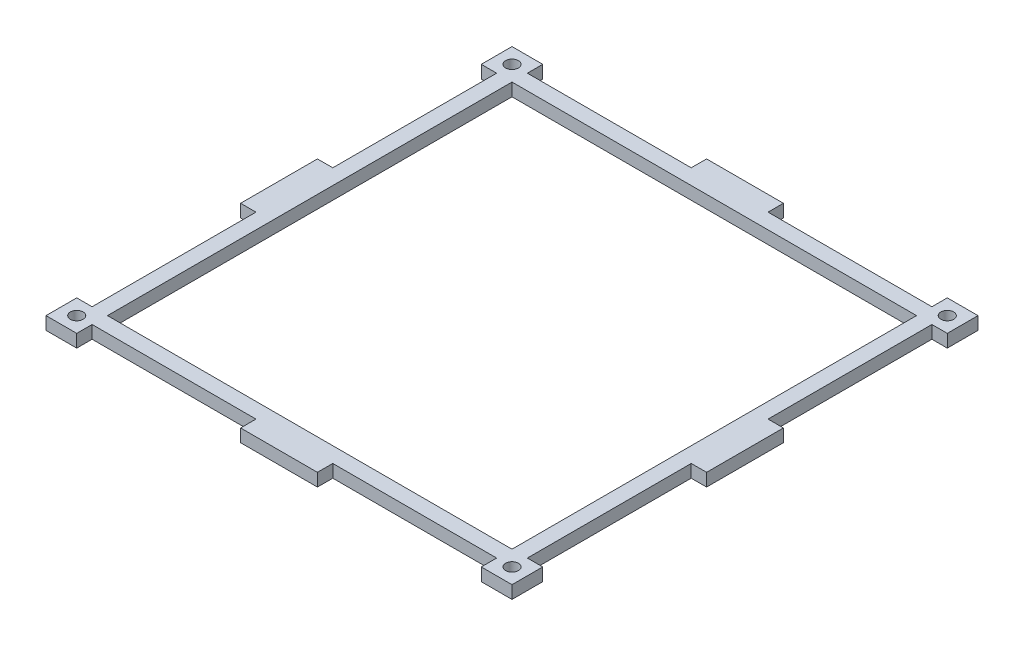
SolidWorks part; units mm, degrees
ref_plane "Alzado" through (0, 0, 0) normal (0, 0, 1) x (1, 0, 0)
ref_plane "Planta" through (0, 0, 0) normal (0, 1, 0) x (1, 0, 0)
ref_plane "Vista lateral" through (0, 0, 0) normal (1, 0, 0) x (0, 0, -1)
sketch "Croquis1" plane through (0, 0, 0) normal (0, 1, 0) x (1, 0, 0)
  line L0 (-79, 79) -> (-91, 91) construction
  line L1 (0, 0) -> (-79, 0) construction
  line L2 (0, 0) -> (0, 79) construction
  line L3 (0, 79) -> (-79, 79)
  line L4 (-79, 0) -> (-79, 79)
  line L5 (0, 0) -> (-85, 0) construction
  line L6 (0, 0) -> (0, 85) construction
  line L7 (-15, 85) -> (-79, 85)
  line L8 (-85, 15) -> (-85, 79)
  line L13 (-85, 79) -> (-91, 79)
  line L14 (-79, 85) -> (-79, 91)
  line L15 (-79, 91) -> (-91, 91)
  line L16 (-91, 79) -> (-91, 91)
  line L17 (-85, 79) -> (-79, 79) construction
  line L18 (-79, 79) -> (-79, 85) construction
  line L19 (-79, 91) -> (-15, 91) construction
  line L22 (0, 91) -> (-15, 91)
  line L23 (-15, 85) -> (-15, 91)
  line L24 (0, 91) -> (0, 79) construction
  line L25 (-15, 85) -> (0, 85) construction
  line L26 (-91, 15) -> (-91, 79) construction
  line L29 (-85, 15) -> (-91, 15)
  line L30 (-91, 0) -> (-91, 15)
  line L31 (-91, 0) -> (-85, 0) construction
  line L32 (-85, 0) -> (-85, 15) construction
  line L33 (-91, 0) -> (-79, 0)
  line L34 (0, 79) -> (0, 91)
  line L35 (79, 0) -> (79, 79)
  line L36 (79, 0) -> (91, 0)
  line L37 (91, 0) -> (91, 15)
  line L38 (85, 15) -> (91, 15)
  line L39 (85, 15) -> (85, 79)
  line L40 (85, 79) -> (91, 79)
  line L41 (91, 79) -> (91, 91)
  line L42 (79, 91) -> (91, 91)
  line L43 (79, 85) -> (79, 91)
  line L44 (15, 85) -> (79, 85)
  line L45 (15, 85) -> (15, 91)
  line L46 (0, 91) -> (15, 91)
  line L47 (0, 91) -> (0, 79)
  line L48 (0, 79) -> (79, 79)
  line L49 (0, -79) -> (79, -79)
  line L50 (0, -79) -> (0, -91)
  line L51 (0, -91) -> (15, -91)
  line L52 (15, -85) -> (15, -91)
  line L53 (15, -85) -> (79, -85)
  line L54 (79, -85) -> (79, -91)
  line L55 (79, -91) -> (91, -91)
  line L56 (91, -79) -> (91, -91)
  line L57 (85, -79) -> (91, -79)
  line L58 (85, -15) -> (85, -79)
  line L59 (85, -15) -> (91, -15)
  line L60 (91, 0) -> (91, -15)
  line L61 (91, 0) -> (79, 0)
  line L62 (79, 0) -> (79, -79)
  line L63 (-79, 0) -> (-79, -79)
  line L64 (-79, 0) -> (-91, 0)
  line L65 (-91, 0) -> (-91, -15)
  line L66 (-85, -15) -> (-91, -15)
  line L67 (-85, -15) -> (-85, -79)
  line L68 (-85, -79) -> (-91, -79)
  line L69 (-91, -79) -> (-91, -91)
  line L70 (-79, -91) -> (-91, -91)
  line L71 (-79, -85) -> (-79, -91)
  line L72 (-15, -85) -> (-79, -85)
  line L73 (-15, -85) -> (-15, -91)
  line L74 (0, -91) -> (-15, -91)
  line L75 (0, -91) -> (0, -79)
  line L76 (0, -79) -> (-79, -79)
  circle A0 centre (-85, 85) radius 2.5
  circle A1 centre (85, 85) radius 2.5
  circle A2 centre (85, -85) radius 2.5
  circle A3 centre (-85, -85) radius 2.5
  dimension "D3" = 5
  dimension "D1" = 79
  dimension "D2" = 6
  dimension "D4" = 85
  dimension "D5" = 15
  dimension "D6" = 4
extrude "Saliente-Extruir1" add sketch "Croquis1" along normal blind 5 contours L34 L48 L35 L36 L37 L38 L39 L40 L41 L42 L43 L44 L45 L46 A1 | L36 L62 L49 L50 L51 L52 L53 L54 L55 L56 L57 L58 L59 L60 A2 | L50 L76 L63 L33 L65 L66 L67 L68 L69 L70 L71 L72 L73 L74 A3 | L3 L34 L22 L23 L7 L14 L15 L16 L13 L8 L29 L30 L33 L4 A0
